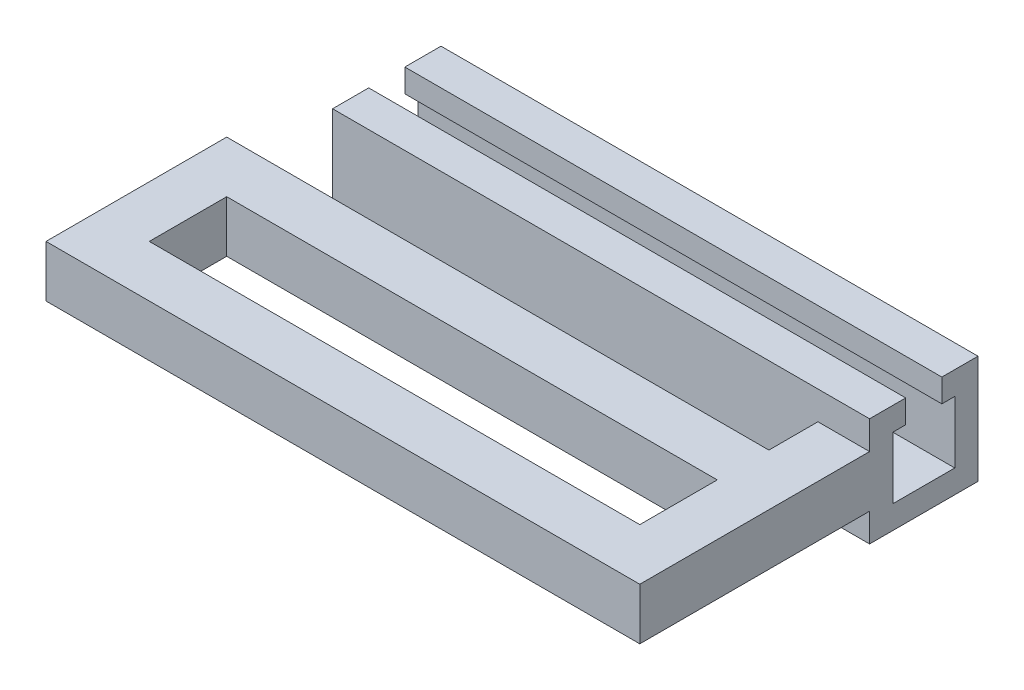
SolidWorks part; units mm, degrees
ref_plane "Plano frontal" through (0, 0, 0) normal (0, 0, 1) x (1, 0, 0)
ref_plane "Plano superior" through (0, 0, 0) normal (0, 1, 0) x (1, 0, 0)
ref_plane "Plano direito" through (0, 0, 0) normal (1, 0, 0) x (0, 0, -1)
sketch "Esboço1" plane through (0, 0, 0) normal (0, 1, 0) x (1, 0, 0)
  line L1 (-10.4795, 11.375) -> (12.5205, 11.375)
  line L2 (-10.4795, 11.375) -> (-10.4795, 9.375)
  line L3 (-10.4795, 9.375) -> (10.5205, 9.375)
  line L6 (12.5205, 11.375) -> (12.5205, -0.625)
  line L7 (12.5205, -0.625) -> (10.5205, -0.625)
  line L8 (10.5205, 9.375) -> (10.5205, 6.375)
  line L9 (10.5205, -0.625) -> (-10.4795, -0.625)
  line L11 (10.5205, 1.375) -> (-8.4795, 1.375)
  line L13 (-10.4795, 6.375) -> (10.5205, 6.375)
  line L14 (-10.4795, 6.375) -> (-10.4795, -0.625)
  line L15 (-8.4795, 4.375) -> (10.5205, 4.375)
  line L17 (-8.4795, 4.375) -> (-8.4795, 1.375)
  line L18 (10.5205, 4.375) -> (10.5205, 1.375)
  dimension "D1" = 2
  dimension "D2" = 23
  dimension "D9" = 19
extrude "Ressalto-extrusão1" add sketch "Esboço1" along normal blind 2
sketch "Esboço3" plane through (0, 0, 0) normal (0, 1, 0) x (1, 0, 0)
  line L11 (-8.4795, 8.4783) -> (-8.4795, 12.0439)
  line L12 (-8.4795, 12.0439) -> (-10.8179, 12.0439)
  line L13 (-10.8179, 8.4783) -> (-10.8179, 12.0439)
  line L14 (-10.8179, 8.4783) -> (-8.4795, 8.4783)
extrude "Corte-extrusão2" cut sketch "Esboço3" along normal blind 3
sketch "Esboço4" plane through (-8.4795, 0, 0) normal (-1, 0, 0) x (0, 0, 1)
  line L0 (-11.375, 0) -> (-9.375, 2) construction
  line L1 (-11.375, 2) -> (-9.375, 0) construction
  line L3 (-11.475, -0.1) -> (-9.275, -0.1)
  line L4 (-11.475, -0.1) -> (-11.475, 2.1)
  line L5 (-11.475, 2.1) -> (-9.275, 2.1)
  line L6 (-9.275, -0.1) -> (-9.275, 2.1)
  line L7 (-11.475, -0.1) -> (-9.275, 2.1) construction
  line L8 (-11.475, 2.1) -> (-9.275, -0.1) construction
  line L9 (-12.475, -1.1) -> (-8.275, -1.1)
  line L10 (-12.475, -1.1) -> (-12.475, 3.1)
  line L11 (-12.475, 3.1) -> (-8.275, 3.1)
  line L12 (-8.275, -1.1) -> (-8.275, 3.1)
  line L13 (-12.475, -1.1) -> (-8.275, 3.1) construction
  line L14 (-12.475, 3.1) -> (-8.275, -1.1) construction
  point P8 (-10.375, 1)
  point P13 (-10.375, 1)
  dimension "D1" = 2.2
  dimension "D2" = 2.2
  dimension "D3" = 1
  dimension "D4" = 1
extrude "Ressalto-extrusão2" add sketch "Esboço4" against normal blind 21
sketch "Esboço5" plane through (-8.4795, 0, 0) normal (-1, 0, 0) x (0, 0, 1)
  line L4 (-9.375, 0) -> (-9.375, 2)
  line L5 (-9.375, 2) -> (-11.375, 2)
  line L6 (-11.375, 2) -> (-11.375, 0)
  line L7 (-11.375, 0) -> (-9.375, 0)
  line L8 (-9.375, 0) -> (-9.375, 2)
  line L9 (-9.375, 2) -> (-11.375, 2)
  line L10 (-11.375, 2) -> (-11.375, 0)
  line L11 (-11.375, 0) -> (-9.375, 0)
  dimension "D1" = 0
extrude "Corte-extrusão3" cut sketch "Esboço5" against normal blind 29
sketch "Esboço6" plane through (0, 0, 0) normal (0, 1, 0) x (1, 0, 0)
  line L1 (-19.0158, 18.6754) -> (-8.2795, 18.6754)
  line L2 (-19.0158, 18.6754) -> (-19.0158, 7.6294)
  line L3 (-19.0158, 7.6294) -> (-8.2795, 7.6294)
  line L4 (-8.2795, 18.6754) -> (-8.2795, 7.6294)
  line L5 (-19.0158, 18.6754) -> (-8.2795, 7.6294) construction
  line L6 (-19.0158, 7.6294) -> (-8.2795, 18.6754) construction
  point P0 (-13.6476, 13.1524)
  dimension "D1" = 0.2
extrude "Corte-extrusão4" cut sketch "Esboço6" against normal mid plane 9
sketch "Esboço7" plane through (-8.2795, 0, 0) normal (-1, 0, 0) x (0, 0, 1)
  line L0 (-11.475, -0.1) -> (-9.275, 2.1) construction
  line L1 (-11.475, 2.1) -> (-9.275, -0.1) construction
  line L2 (-11.075, 2.2) -> (-11.075, 3.37)
  line L3 (-11.575, -0.2) -> (-9.175, -0.2)
  line L4 (-11.575, -0.2) -> (-11.575, 2.2)
  line L5 (-11.575, 2.2) -> (-11.075, 2.2)
  line L6 (-9.175, -0.2) -> (-9.175, 2.2)
  line L7 (-11.575, -0.2) -> (-9.175, 2.2) construction
  line L8 (-11.575, 2.2) -> (-9.175, -0.2) construction
  line L9 (-11.075, 3.37) -> (-9.675, 3.37)
  line L10 (-9.675, 2.2) -> (-9.675, 3.37)
  line L11 (-9.675, 2.2) -> (-9.175, 2.2)
  point P8 (-10.375, 1)
  dimension "D1" = 2.4
  dimension "D2" = 2.4
  dimension "D3" = 0.5
  dimension "D4" = 0.5
extrude "Corte-extrusão5" cut sketch "Esboço7" against normal blind 24
